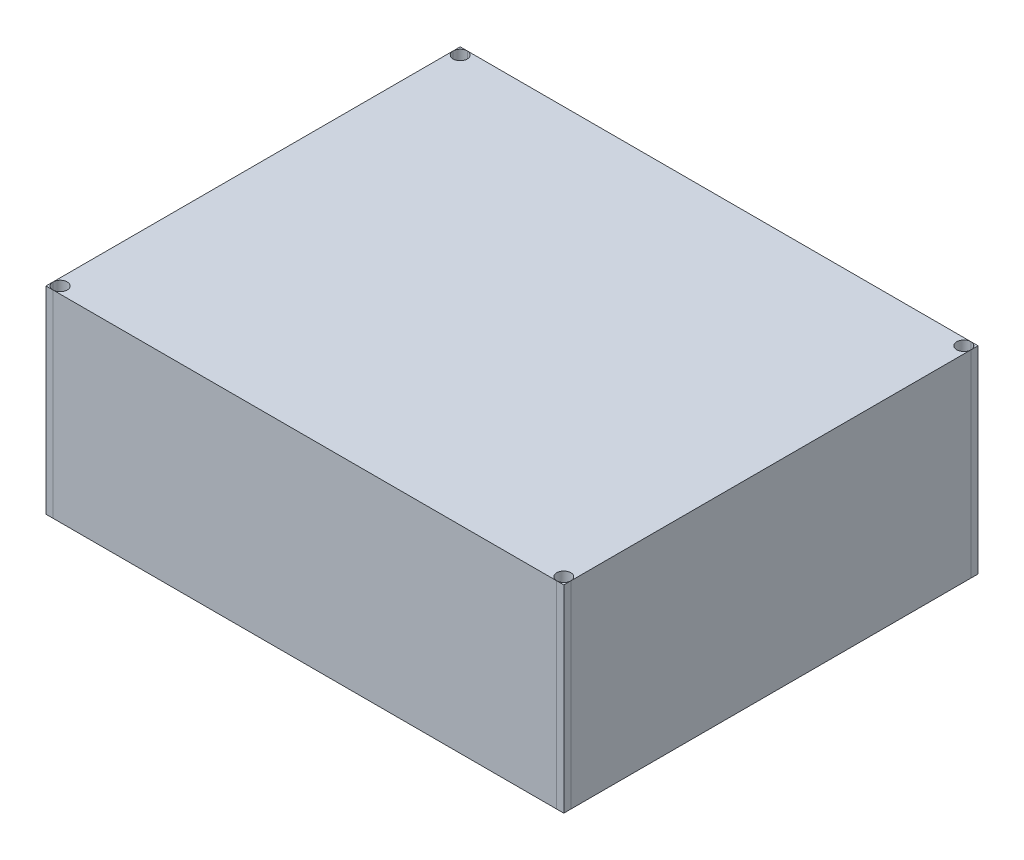
SolidWorks part; units mm, degrees
ref_plane "前基準面" through (0, 0, 0) normal (0, 0, 1) x (1, 0, 0)
ref_plane "上基準面" through (0, 0, 0) normal (0, 1, 0) x (1, 0, 0)
ref_plane "右基準面" through (0, 0, 0) normal (1, 0, 0) x (0, 0, -1)
sketch "草圖1" plane through (0, 0, 0) normal (0, 1, 0) x (1, 0, 0)
  line L1 (55, 44) -> (-55, 44)
  line L2 (55, 44) -> (55, -44)
  line L3 (55, -44) -> (-55, -44)
  line L4 (-55, 44) -> (-55, -44)
  line L5 (0, -44) -> (0, 44) construction
  line L6 (55, 0) -> (-55, 0) construction
  circle A0 centre (-53.5, -42.5) radius 1.5 construction
  circle A1 centre (-53.5, 42.5) radius 1.5 construction
  circle A2 centre (53.5, 42.5) radius 1.5 construction
  circle A3 centre (53.5, -42.5) radius 1.5 construction
  point P0 (0, 0)
  point P6 (-51.5733, -41.2932)
  point P16 (0, 0)
  point P17 (0, 0)
  dimension "D3" = 3
  dimension "D1" = 110
  dimension "D2" = 88
extrude "填料-伸長1" add sketch "草圖1" along normal blind 42
sketch "草圖3" plane through (0, 42, 0) normal (0, 1, 0) x (1, 0, 0)
  circle A0 centre (53.5, -42.5) radius 1.5 construction
  circle A1 centre (53.5, 42.5) radius 1.5 construction
  circle A2 centre (-53.5, 42.5) radius 1.5 construction
  circle A3 centre (-53.5, -42.5) radius 1.5 construction
  circle A4 centre (53.5, -42.5) radius 1.5
  circle A5 centre (53.5, 42.5) radius 1.5
  circle A6 centre (-53.5, 42.5) radius 1.5
  circle A7 centre (-53.5, -42.5) radius 1.5
extrude "除料-伸長1" cut sketch "草圖3" against normal through all
